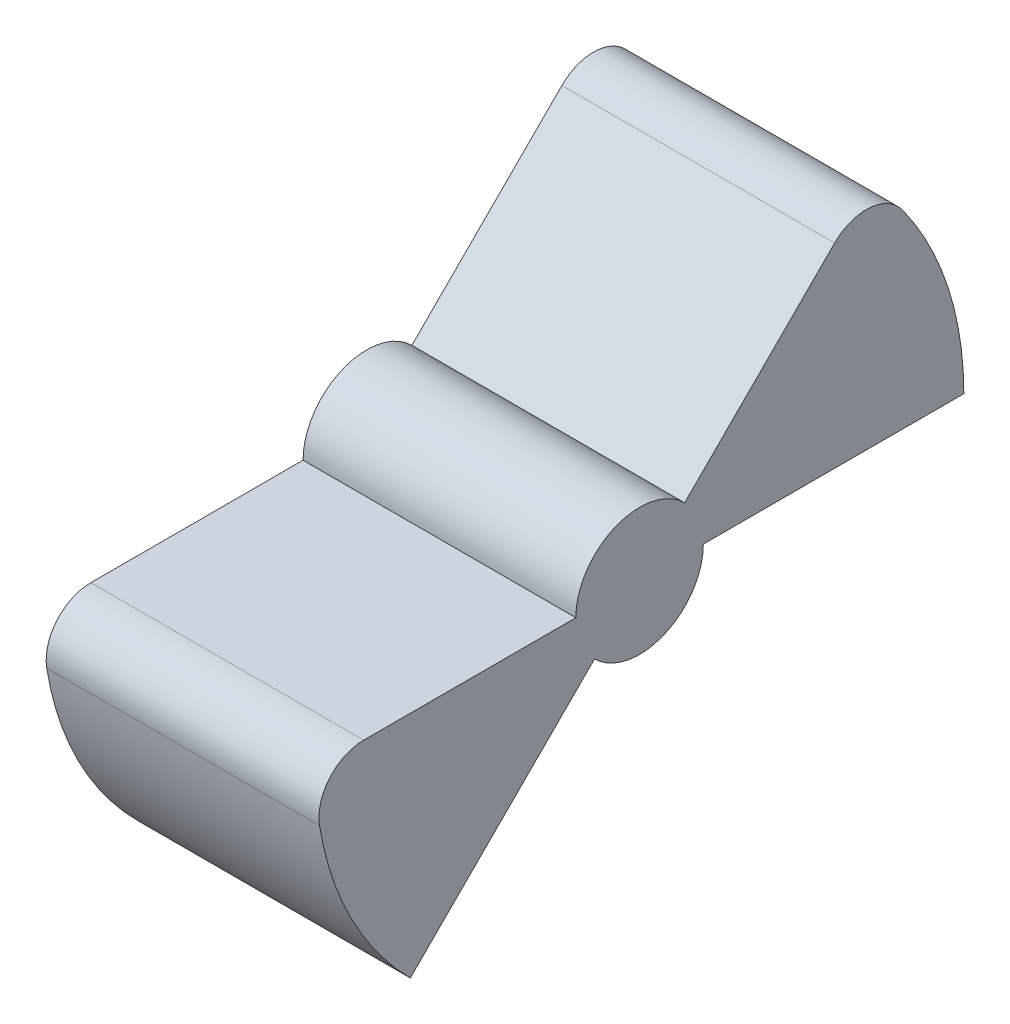
SolidWorks part; units mm, degrees
ref_plane "Front Plane" through (0, 0, 0) normal (0, 0, 1) x (1, 0, 0)
ref_plane "Top Plane" through (0, 0, 0) normal (0, 1, 0) x (1, 0, 0)
ref_plane "Right Plane" through (0, 0, 0) normal (1, 0, 0) x (0, 0, -1)
sketch "Sketch1" plane through (0, 0, 0) normal (0, 1, 0) x (1, 0, 0)
  line L1 (-6.25, -14.5) -> (6.25, -14.5)
  line L2 (-6.25, -14.5) -> (-6.25, 14.5)
  line L3 (-6.25, 14.5) -> (6.25, 14.5)
  line L4 (6.25, -14.5) -> (6.25, 14.5)
  line L5 (-6.25, -14.5) -> (6.25, 14.5) construction
  line L6 (-6.25, 14.5) -> (6.25, -14.5) construction
  point P0 (0, 0)
  dimension "D1" = 12.5
  dimension "D2" = 29
sketch "Sketch2" plane through (0, 0, 0) normal (1, 0, 0) x (0, 0, -1)
  line L0 (2.0153, 2.0153) -> (8.725, 8.725)
  line L1 (14.5, 0) -> (-14.5, 0) construction
  line L2 (-2.0153, -2.0153) -> (-10.253, -10.253)
  line L3 (14.5, 0) -> (2.85, 0)
  line L4 (-2.85, 0) -> (-12.339, 0)
  arc A0 (-14.3132, -2.32) -> (-10.253, -10.253) centre (0, 0) ccw
  arc A1 (14.5, 0) -> (11.7614, 8.4805) centre (0, 0) ccw
  arc A2 (2.0153, 2.0153) -> (-2.85, 0) centre (0, 0) ccw
  arc A3 (-2.0153, -2.0153) -> (2.85, 0) centre (0, 0) ccw
  arc A4 (-12.339, 0) -> (-14.3132, -2.32) centre (-12.339, -2) ccw
  arc A5 (8.725, 8.725) -> (11.7614, 8.4805) centre (10.1392, 7.3108) cw
  point P14 (-14.5, 0)
  dimension "D2" = 5.7
  dimension "D3" = 2
  dimension "D1" = 45
extrude "Boss-Extrude1" add sketch "Sketch2" along normal mid plane 12.2
